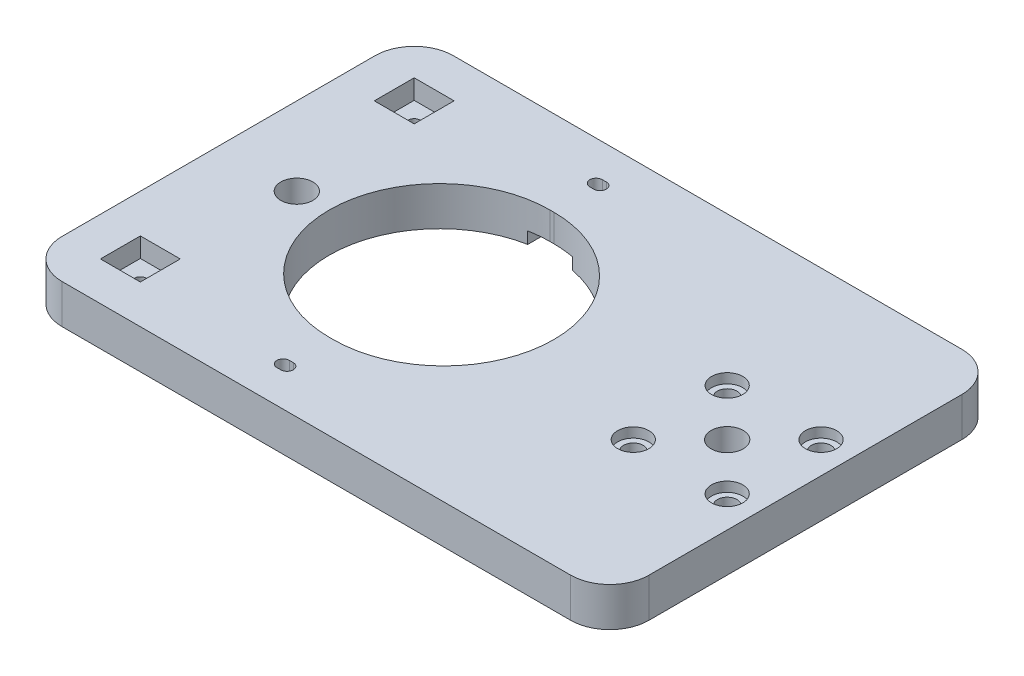
SolidWorks part; units mm, degrees
ref_plane "正面" through (0, 0, 0) normal (0, 0, 1) x (1, 0, 0)
ref_plane "平面" through (0, 0, 0) normal (0, 1, 0) x (1, 0, 0)
ref_plane "右側面" through (0, 0, 0) normal (1, 0, 0) x (0, 0, -1)
sketch "ｽｹｯﾁ1" plane through (0, 0, 0) normal (0, 1, 0) x (1, 0, 0)
  line L1 (-65, -50) -> (65, -50)
  line L2 (-75, -40) -> (-75, 40)
  line L3 (-65, 50) -> (65, 50)
  line L4 (75, -40) -> (75, 40)
  line L5 (-75, -50) -> (75, 50) construction
  line L6 (-75, 50) -> (75, -50) construction
  circle A0 centre (55, 0) radius 4.1
  circle A1 centre (43, 12) radius 2.5
  circle A2 centre (67, 12) radius 2.5
  circle A3 centre (67, -12) radius 2.5
  circle A4 centre (43, -12) radius 2.5
  arc A5 (65, 50) -> (75, 40) centre (65, 40) cw
  arc A6 (65, -50) -> (75, -40) centre (65, -40) ccw
  arc A7 (-65, -50) -> (-75, -40) centre (-65, -40) cw
  arc A8 (-75, 40) -> (-65, 50) centre (-65, 40) cw
  circle A9 centre (-55, 0) radius 4.1
  point P0 (0, 0)
  dimension "D3" = 8.2
  dimension "D9" = 5
  dimension "D10" = 10
  dimension "D11" = 8.2
  dimension "D1" = 150
  dimension "D2" = 100
  dimension "D4" = 20
  dimension "D5" = 24
  dimension "D6" = 24
  dimension "D7" = 12
  dimension "D8" = 12
  dimension "D12" = 20
extrude "ﾎﾞｽ - 押し出し1" add sketch "ｽｹｯﾁ1" along normal blind 10
sketch "ｽｹｯﾁ5" plane through (0, 10, 0) normal (0, 1, 0) x (1, 0, 0)
  line L0 (-18.5, 0) -> (-17.5, 0) construction
  line L3 (-18.5, 28.2) -> (-17.5, 28.2)
  line L10 (-18.5, 40) -> (-17.5, 40) construction
  line L11 (-18.5, 41.6) -> (-17.5, 41.6)
  line L12 (-18.5, 38.4) -> (-17.5, 38.4)
  line L13 (-18.5, -40) -> (-17.5, -40) construction
  line L14 (-18.5, -38.4) -> (-17.5, -38.4)
  line L15 (-18.5, -41.6) -> (-17.5, -41.6)
  line L16 (-18.5, -28.2) -> (-17.5, -28.2)
  arc A6 (-18.5, 28.2) -> (-18.5, -28.2) centre (-18.5, 0) ccw
  circle A7 centre (-55, 0) radius 4.1 construction
  arc A11 (-18.5, 41.6) -> (-18.5, 38.4) centre (-18.5, 40) ccw
  arc A12 (-17.5, 38.4) -> (-17.5, 41.6) centre (-17.5, 40) ccw
  arc A13 (-18.5, -38.4) -> (-18.5, -41.6) centre (-18.5, -40) ccw
  arc A14 (-17.5, -41.6) -> (-17.5, -38.4) centre (-17.5, -40) ccw
  arc A15 (-17.5, -28.2) -> (-17.5, 28.2) centre (-17.5, 0) ccw
  point P2 (-18, 0)
  point P7 (0, 0)
  point P8 (0, 0)
  point P11 (0, 0)
  point P14 (-18, 40)
  point P20 (-18, -40)
  dimension "D3" = 37
  dimension "D4" = 1
  dimension "D2" = 28.2
  dimension "D5" = 40
  dimension "D6" = 3.2
  dimension "D7" = 3.2
  dimension "D8" = 40
extrude "ｶｯﾄ - 押し出し3" cut sketch "ｽｹｯﾁ5" against normal up to next
sketch "ｽｹｯﾁ6" plane through (0, 0, 0) normal (0, 1, 0) x (1, 0, 0)
  line L0 (-18.5, 40) -> (-17.5, 40) construction
  line L1 (-18.5, 45.2) -> (-17.5, 45.2)
  line L3 (-18.5, -40) -> (-17.5, -40) construction
  line L5 (-18.5, -45.2) -> (-17.5, -45.2)
  line L6 (-18.5, 0) -> (-17.5, 0) construction
  line L9 (-23.7, 40) -> (-23.7, 27.7164)
  line L10 (-12.3, 40) -> (-12.3, 27.7164)
  line L11 (-23.7, -40) -> (-23.7, -27.7164)
  line L12 (-12.3, -40) -> (-12.3, -27.7164)
  arc A0 (-18.5, 45.2) -> (-23.7, 40) centre (-18.5, 40) ccw
  arc A1 (-12.3, 40) -> (-17.5, 45.2) centre (-17.5, 40) ccw
  arc A2 (-23.7, -40) -> (-18.5, -45.2) centre (-18.5, -40) ccw
  arc A3 (-17.5, -45.2) -> (-12.3, -40) centre (-17.5, -40) ccw
  arc A4 (-23.7, 27.7164) -> (-23.7, -27.7164) centre (-18.5, 0) ccw
  arc A5 (-12.3, -27.7164) -> (-12.3, 27.7164) centre (-17.5, 0) ccw
  circle A6 centre (-55, 0) radius 4.1 construction
  point P3 (-18, 40)
  point P8 (-18, -40)
  point P17 (-18, 0)
  dimension "D2" = 37
  dimension "D4" = 5.2
  dimension "D3" = 28.2
  dimension "D1" = 1
  dimension "D5" = 40
  dimension "D6" = 40
extrude "ｶｯﾄ - 押し出し4" cut sketch "ｽｹｯﾁ6" along normal blind 3
sketch "ｽｹｯﾁ7" plane through (0, 0, 0) normal (0, -1, 0) x (1, 0, 0)
  circle A0 centre (20, 0) radius 5.1
  dimension "D1" = 10.2
  dimension "D2" = 20
extrude "ｶｯﾄ - 押し出し5" cut sketch "ｽｹｯﾁ7" against normal blind 5
sketch "ｽｹｯﾁ8" plane through (0, 10, 0) normal (0, 1, 0) x (1, 0, 0)
  circle A0 centre (43, 12) radius 4
  circle A1 centre (67, 12) radius 4
  circle A2 centre (43, -12) radius 4
  circle A3 centre (67, -12) radius 4
  dimension "D1" = 8
extrude "ｶｯﾄ - 押し出し6" cut sketch "ｽｹｯﾁ8" against normal blind 2.5
sketch "ｽｹｯﾁ9" plane through (0, 10, 0) normal (0, 1, 0) x (1, 0, 0)
  line L0 (-75, 40) -> (-75, -40) construction
  line L1 (-65, -50) -> (65, -50) construction
  line L2 (65, 50) -> (-65, 50) construction
  circle A0 centre (-60, 35) radius 1.5
  circle A1 centre (-60, -35) radius 1.5
  point P10 (0, 0)
  dimension "D4" = 3
  dimension "D1" = 15
  dimension "D2" = 15
  dimension "D3" = 15
extrude "ｶｯﾄ - 押し出し7" cut sketch "ｽｹｯﾁ9" against normal through all
sketch "ｽｹｯﾁ10" plane through (0, 10, 0) normal (0, 1, 0) x (1, 0, 0)
  line L1 (-65.1, 29.9) -> (-54.9, 29.9)
  line L2 (-65.1, 29.9) -> (-65.1, 40.1)
  line L3 (-65.1, 40.1) -> (-54.9, 40.1)
  line L4 (-54.9, 29.9) -> (-54.9, 40.1)
  line L5 (-65.1, 29.9) -> (-54.9, 40.1) construction
  line L6 (-65.1, 40.1) -> (-54.9, 29.9) construction
  line L7 (-65.1, -40.1) -> (-54.9, -40.1)
  line L8 (-65.1, -40.1) -> (-65.1, -29.9)
  line L9 (-65.1, -29.9) -> (-54.9, -29.9)
  line L10 (-54.9, -40.1) -> (-54.9, -29.9)
  line L11 (-65.1, -40.1) -> (-54.9, -29.9) construction
  line L12 (-65.1, -29.9) -> (-54.9, -40.1) construction
  point P0 (-60, 35)
  point P6 (-60, -35)
  dimension "D1" = 10.2
extrude "ｶｯﾄ - 押し出し8" cut sketch "ｽｹｯﾁ10" against normal blind 5
